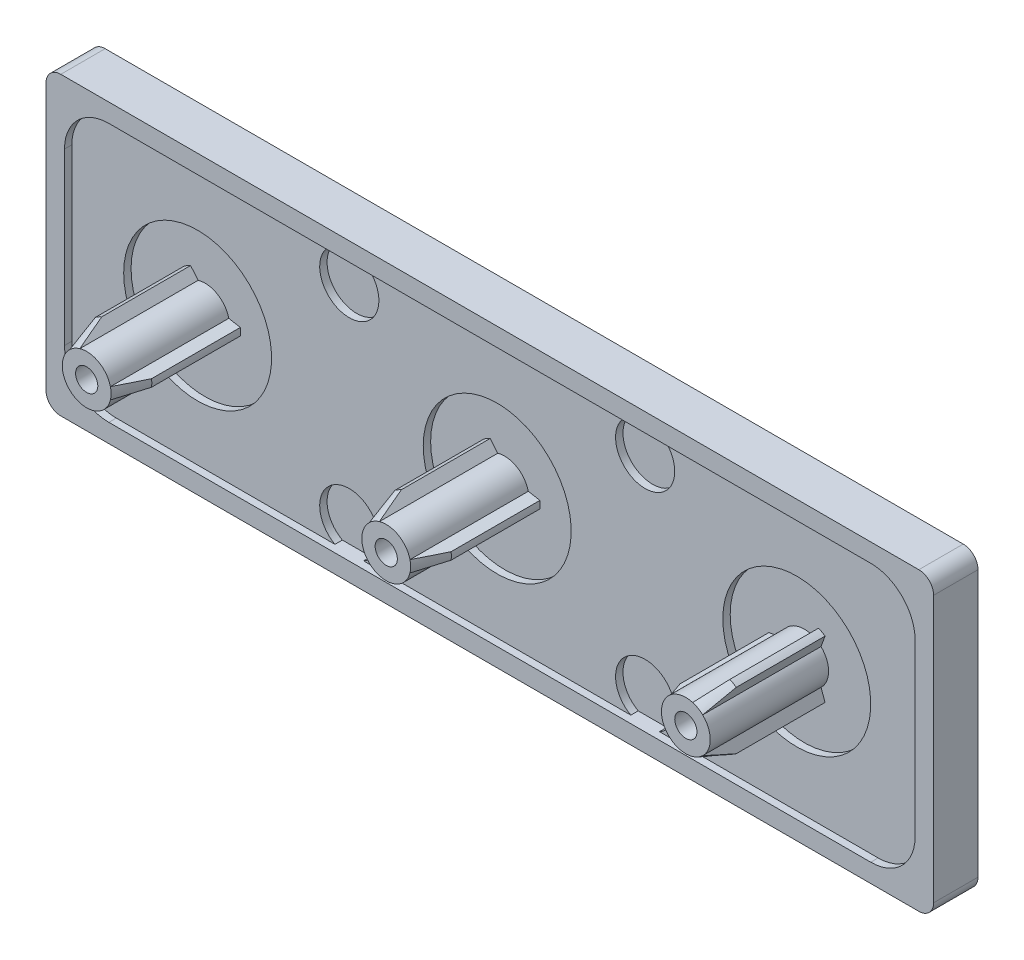
SolidWorks part; units mm, degrees
material "PA Type 6"
ref_plane "Front Plane" through (0, 0, 0) normal (0, 0, 1) x (1, 0, 0)
ref_plane "Top Plane" through (0, 0, 0) normal (0, 1, 0) x (1, 0, 0)
ref_plane "Right Plane" through (0, 0, 0) normal (1, 0, 0) x (0, 0, -1)
ref_plane "Plane1" through (0, 0, 0) normal (0, 0, 1) x (1, 0, 0)
sketch "Sketch1" plane through (0, 0, 0) normal (0, 0, 1) x (1, 0, 0)
  line L0 (-29, -10) -> (29, -10)
  line L1 (30, -9) -> (30, 9)
  line L2 (29, 10) -> (-29, 10)
  line L3 (-30, 9) -> (-30, -9)
  arc A0 (-30, -9) -> (-29, -10) centre (-29, -9) ccw
  arc A1 (29, -10) -> (30, -9) centre (29, -9) ccw
  arc A2 (30, 9) -> (29, 10) centre (29, 9) ccw
  arc A3 (-29, 10) -> (-30, 9) centre (-29, 9) ccw
extrude "Boss-Extrude1" add sketch "Sketch1" against normal blind 3
ref_plane "Plane2" through (0, 0, 0) normal (0, 0, 1) x (1, 0, 0)
sketch "Sketch2" plane through (0, 0, 0) normal (0, 0, 1) x (1, 0, 0)
  line L0 (-25.75, -8.75) -> (25.75, -8.75)
  line L1 (28.75, -5.75) -> (28.75, 5.75)
  line L2 (25.75, 8.75) -> (-25.75, 8.75)
  line L3 (-28.75, 5.75) -> (-28.75, -5.75)
  arc A0 (-28.75, -5.75) -> (-25.75, -8.75) centre (-25.75, -5.75) ccw
  arc A1 (25.75, -8.75) -> (28.75, -5.75) centre (25.75, -5.75) ccw
  arc A2 (28.75, 5.75) -> (25.75, 8.75) centre (25.75, 5.75) ccw
  arc A3 (-25.75, 8.75) -> (-28.75, 5.75) centre (-25.75, 5.75) ccw
extrude "Cut-Extrude1" cut sketch "Sketch2" against normal blind 0.5
ref_plane "Plane3" through (0, 0, 0) normal (0, 1, 0) x (1, 0, 0)
sketch "Sketch3" plane through (0, 0, 0) normal (0, 1, 0) x (1, 0, 0)
  line L0 (-20.25, 1) -> (-15.25, 1)
  line L1 (-15.25, 1) -> (-15.25, 0.5)
  line L2 (-15.25, 0.5) -> (-20.25, 0.5)
  line L3 (-20.25, 0.5) -> (-20.25, 1)
  line L4 (-20.25, 0.5) -> (-20.25, 1) construction
revolve "Cut-Revolve1" cut sketch "Sketch3" angle 360 about L4
ref_plane "Plane4" through (0, 0, 0) normal (0, 1, 0) x (1, 0, 0)
sketch "Sketch4" plane through (0, 0, 0) normal (0, 1, 0) x (1, 0, 0)
  line L0 (0, 1) -> (5, 1)
  line L1 (5, 1) -> (5, 0.5)
  line L2 (5, 0.5) -> (0, 0.5)
  line L3 (0, 0.5) -> (0, 1)
  line L4 (0, 0.5) -> (0, 1) construction
revolve "Cut-Revolve2" cut sketch "Sketch4" angle 360 about L4
ref_plane "Plane5" through (0, 0, 0) normal (0, 1, 0) x (1, 0, 0)
sketch "Sketch5" plane through (0, 0, 0) normal (0, 1, 0) x (1, 0, 0)
  line L0 (20.25, 1) -> (25.25, 1)
  line L1 (25.25, 1) -> (25.25, 0.5)
  line L2 (25.25, 0.5) -> (20.25, 0.5)
  line L3 (20.25, 0.5) -> (20.25, 1)
  line L4 (20.25, 0.5) -> (20.25, 1) construction
revolve "Cut-Revolve3" cut sketch "Sketch5" angle 360 about L4
ref_plane "Plane6" through (0, 0, -0.5) normal (0, 0, 1) x (1, 0, 0)
sketch "Sketch6" plane through (0, 0, -0.5) normal (0, 0, 1) x (1, 0, 0)
  line L0 (-9.0318, 8.75) -> (-10.9682, 8.75)
  arc A0 (-10.9682, 8.75) -> (-9.0318, 8.75) centre (-10, 7) ccw
extrude "Cut-Extrude2" cut sketch "Sketch6" against normal blind 0.5
ref_plane "Plane7" through (0, 0, -0.5) normal (0, 0, 1) x (1, 0, 0)
sketch "Sketch7" plane through (0, 0, -0.5) normal (0, 0, 1) x (1, 0, 0)
  line L0 (10.9682, 8.75) -> (9.0318, 8.75)
  arc A0 (9.0318, 8.75) -> (10.9682, 8.75) centre (10, 7) ccw
extrude "Cut-Extrude3" cut sketch "Sketch7" against normal blind 0.5
ref_plane "Plane8" through (0, 0, -0.5) normal (0, 0, 1) x (1, 0, 0)
sketch "Sketch8" plane through (0, 0, -0.5) normal (0, 0, 1) x (1, 0, 0)
  line L0 (-10.9682, -8.75) -> (-9.0318, -8.75)
  arc A0 (-9.0318, -8.75) -> (-10.9682, -8.75) centre (-10, -7) ccw
extrude "Cut-Extrude4" cut sketch "Sketch8" against normal blind 0.5
ref_plane "Plane9" through (0, 0, -0.5) normal (0, 0, 1) x (1, 0, 0)
sketch "Sketch9" plane through (0, 0, -0.5) normal (0, 0, 1) x (1, 0, 0)
  line L0 (9.0318, -8.75) -> (10.9682, -8.75)
  arc A0 (10.9682, -8.75) -> (9.0318, -8.75) centre (10, -7) ccw
extrude "Cut-Extrude5" cut sketch "Sketch9" against normal blind 0.5
ref_plane "Plane10" through (0, 0, -1) normal (0, 0, 1) x (1, 0, 0)
sketch "Sketch10" plane through (0, 0, -1) normal (0, 0, 1) x (1, 0, 0)
  line L0 (-1.1394, -1.1935) -> (-1.41, -1.9422)
  line L1 (-0.977, -2.1922) -> (-0.4639, -1.5835)
  line L2 (1.6032, -0.39) -> (2.3869, -0.25)
  line L3 (2.3869, 0.25) -> (1.6032, 0.39)
  line L4 (-0.4639, 1.5835) -> (-0.977, 2.1922)
  line L5 (-1.41, 1.9422) -> (-1.1394, 1.1935)
  arc A0 (-1.1394, 1.1935) -> (-1.1394, -1.1935) centre (0, 0) ccw
  arc A1 (-1.41, -1.9422) -> (-0.977, -2.1922) centre (0, 0) ccw
  arc A2 (-0.4639, -1.5835) -> (1.6032, -0.39) centre (0, 0) ccw
  arc A3 (2.3869, -0.25) -> (2.3869, 0.25) centre (0, 0) ccw
  arc A4 (1.6032, 0.39) -> (-0.4639, 1.5835) centre (0, 0) ccw
  arc A5 (-0.977, 2.1922) -> (-1.41, 1.9422) centre (0, 0) ccw
extrude "Boss-Extrude2" add sketch "Sketch10" along normal blind 8
ref_plane "Plane11" through (0, 0, -1) normal (0, 0, 1) x (1, 0, 0)
sketch "Sketch11" plane through (0, 0, -1) normal (0, 0, 1) x (1, 0, 0)
  line L0 (-21.3894, -1.1935) -> (-21.66, -1.9422)
  line L1 (-21.227, -2.1922) -> (-20.7139, -1.5835)
  line L2 (-18.6468, -0.39) -> (-17.8631, -0.25)
  line L3 (-17.8631, 0.25) -> (-18.6468, 0.39)
  line L4 (-20.7139, 1.5835) -> (-21.227, 2.1922)
  line L5 (-21.66, 1.9422) -> (-21.3894, 1.1935)
  arc A0 (-21.3894, 1.1935) -> (-21.3894, -1.1935) centre (-20.25, 0) ccw
  arc A1 (-21.66, -1.9422) -> (-21.227, -2.1922) centre (-20.25, 0) ccw
  arc A2 (-20.7139, -1.5835) -> (-18.6468, -0.39) centre (-20.25, 0) ccw
  arc A3 (-17.8631, -0.25) -> (-17.8631, 0.25) centre (-20.25, 0) ccw
  arc A4 (-18.6468, 0.39) -> (-20.7139, 1.5835) centre (-20.25, 0) ccw
  arc A5 (-21.227, 2.1922) -> (-21.66, 1.9422) centre (-20.25, 0) ccw
extrude "Boss-Extrude3" add sketch "Sketch11" along normal blind 8
ref_plane "Plane12" through (0, 0, -1) normal (0, 0, 1) x (1, 0, 0)
sketch "Sketch12" plane through (0, 0, -1) normal (0, 0, 1) x (1, 0, 0)
  line L0 (17.8631, -0.25) -> (18.6468, -0.39)
  line L1 (20.7139, -1.5835) -> (21.227, -2.1922)
  line L2 (21.66, -1.9422) -> (21.3894, -1.1935)
  line L3 (21.3894, 1.1935) -> (21.66, 1.9422)
  line L4 (21.227, 2.1922) -> (20.7139, 1.5835)
  line L5 (18.6468, 0.39) -> (17.8631, 0.25)
  arc A0 (17.8631, 0.25) -> (17.8631, -0.25) centre (20.25, 0) ccw
  arc A1 (18.6468, -0.39) -> (20.7139, -1.5835) centre (20.25, 0) ccw
  arc A2 (21.227, -2.1922) -> (21.66, -1.9422) centre (20.25, 0) ccw
  arc A3 (21.3894, -1.1935) -> (21.3894, 1.1935) centre (20.25, 0) ccw
  arc A4 (21.66, 1.9422) -> (21.227, 2.1922) centre (20.25, 0) ccw
  arc A5 (20.7139, 1.5835) -> (18.6468, 0.39) centre (20.25, 0) ccw
extrude "Boss-Extrude4" add sketch "Sketch12" along normal blind 8
ref_plane "Plane13" through (0, 0, 0) normal (0, 1, 0) x (1, 0, 0)
sketch "Sketch13" plane through (0, 0, 0) normal (0, 1, 0) x (1, 0, 0)
  line L0 (-18.7125, -7.3) -> (-17.55, -7.3)
  line L1 (-17.55, -7.3) -> (-17.55, -4.2)
  line L2 (-17.55, -4.2) -> (-18.7125, -7.3)
  line L3 (-20.25, -50) -> (-20.25, 50) construction
revolve "Cut-Revolve4" cut sketch "Sketch13" angle 360 about L3
ref_plane "Plane14" through (0, 0, 0) normal (0, 1, 0) x (1, 0, 0)
sketch "Sketch14" plane through (0, 0, 0) normal (0, 1, 0) x (1, 0, 0)
  line L0 (1.5375, -7.3) -> (2.7, -7.3)
  line L1 (2.7, -7.3) -> (2.7, -4.2)
  line L2 (2.7, -4.2) -> (1.5375, -7.3)
  line L3 (0, -50) -> (0, 50) construction
revolve "Cut-Revolve5" cut sketch "Sketch14" angle 360 about L3
ref_plane "Plane15" through (0, 0, 0) normal (0, 1, 0) x (1, 0, 0)
sketch "Sketch15" plane through (0, 0, 0) normal (0, 1, 0) x (1, 0, 0)
  line L0 (21.7875, -7.3) -> (22.95, -7.3)
  line L1 (22.95, -7.3) -> (22.95, -4.2)
  line L2 (22.95, -4.2) -> (21.7875, -7.3)
  line L3 (20.25, -50) -> (20.25, 50) construction
revolve "Cut-Revolve6" cut sketch "Sketch15" angle 360 about L3
ref_plane "Plane16" through (0, 0, 0) normal (0, 1, 0) x (1, 0, 0)
sketch "Sketch16" plane through (0, 0, 0) normal (0, 1, 0) x (1, 0, 0)
  line L0 (-20.25, 1) -> (-19.5, 1)
  line L1 (-19.5, 1) -> (-19.5, -7)
  line L2 (-19.5, -7) -> (-20.25, -7)
  line L3 (-20.25, -7) -> (-20.25, 1)
  line L4 (-20.25, -7) -> (-20.25, 1) construction
revolve "Cut-Revolve7" cut sketch "Sketch16" angle 360 about L4
ref_plane "Plane17" through (0, 0, 0) normal (0, 1, 0) x (1, 0, 0)
sketch "Sketch17" plane through (0, 0, 0) normal (0, 1, 0) x (1, 0, 0)
  line L0 (0, 1) -> (0.75, 1)
  line L1 (0.75, 1) -> (0.75, -7)
  line L2 (0.75, -7) -> (0, -7)
  line L3 (0, -7) -> (0, 1)
  line L4 (0, -7) -> (0, 1) construction
revolve "Cut-Revolve8" cut sketch "Sketch17" angle 360 about L4
ref_plane "Plane18" through (0, 0, 0) normal (0, 1, 0) x (1, 0, 0)
sketch "Sketch18" plane through (0, 0, 0) normal (0, 1, 0) x (1, 0, 0)
  line L0 (20.25, 1) -> (21, 1)
  line L1 (21, 1) -> (21, -7)
  line L2 (21, -7) -> (20.25, -7)
  line L3 (20.25, -7) -> (20.25, 1)
  line L4 (20.25, -7) -> (20.25, 1) construction
revolve "Cut-Revolve9" cut sketch "Sketch18" angle 360 about L4
